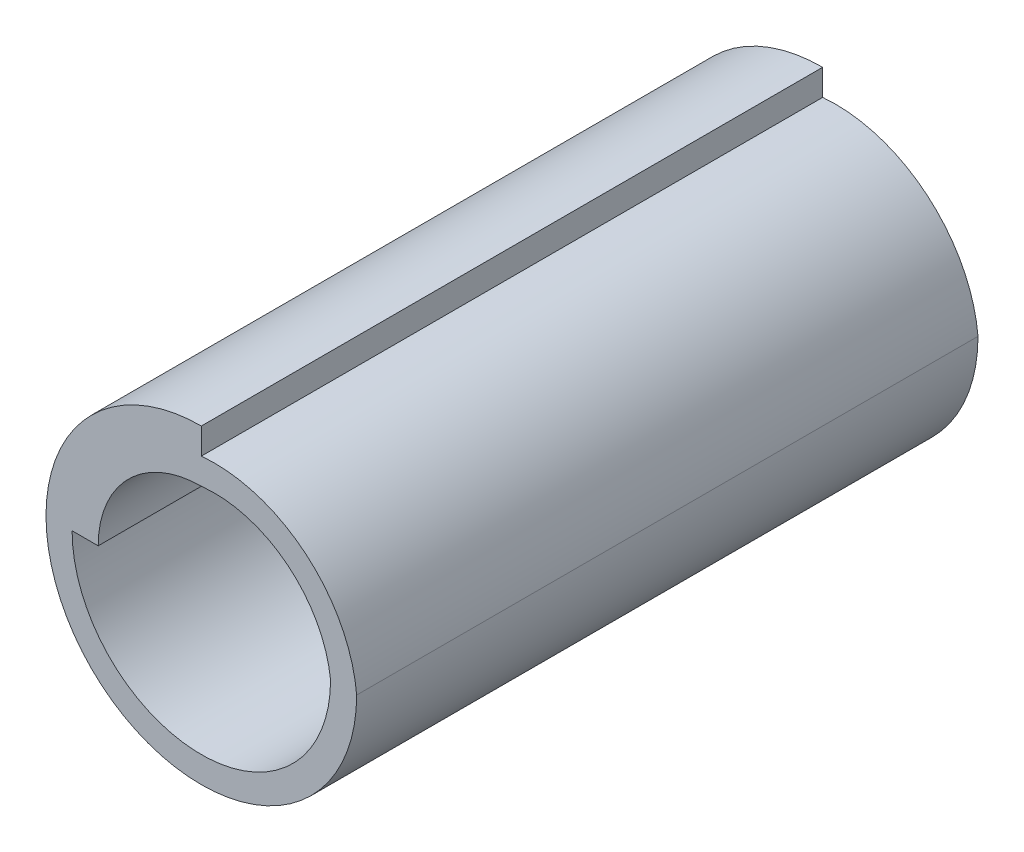
SolidWorks part; units mm, degrees
ref_plane "Plane1" through (0, 0, 0) normal (0, 0, 1) x (1, 0, 0)
ref_plane "Plane2" through (0, 0, 0) normal (0, 1, 0) x (1, 0, 0)
ref_plane "Plane3" through (0, 0, 0) normal (1, 0, 0) x (0, 0, -1)
sketch "Sketch1" plane through (0, 0, 0) normal (0, 0, 1) x (1, 0, 0)
  line L0 (0, 4.16) -> (0, 5)
  line L1 (-4.16, 0) -> (-3.32, 0)
  line L2 (0, 3.32) -> (4.16, 0) construction
  line L3 (0.42, -0.42) -> (2.08, 1.66) construction
  line L4 (0, 4.16) -> (5, 0) construction
  line L5 (0.42, -0.42) -> (2.5, 2.08) construction
  arc A0 (0, 5) -> (5, 0) centre (0, 0) ccw
  arc A1 (-4.16, 0) -> (4.16, 0) centre (0, 0) ccw
  arc A2 (0, 3.32) -> (-3.32, 0) centre (0, 0) ccw
  arc A3 (4.16, 0) -> (0, 3.32) centre (0.42, -0.42) ccw
  arc A4 (5, 0) -> (0, 4.16) centre (0.42, -0.42) ccw
  dimension "Diameter" = 10
  dimension "D2" = 8.32
  dimension "Thickness" = 0.84
  dimension "D1" = 0.84
extrude "Base-Extrude" add sketch "Sketch1" along normal mid plane 20
equation "\"D1@Sketch1\" = \"Thickness@Sketch1\""
equation "\"D2@Sketch1\" = \"Diameter@Sketch1\" - \"Thickness@Sketch1\" * 2"
